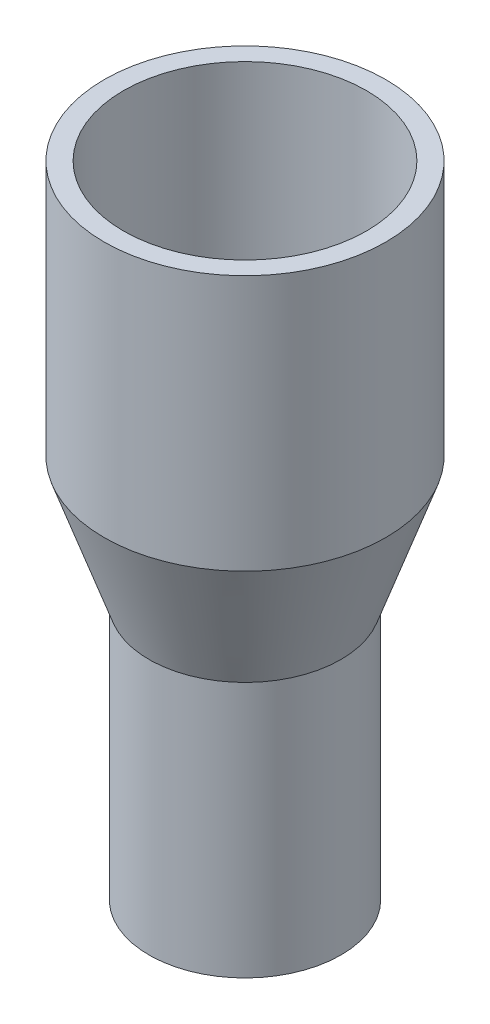
SolidWorks part; units mm, degrees
ref_plane "Front Plane" through (0, 0, 0) normal (0, 0, 1) x (1, 0, 0)
ref_plane "Top Plane" through (0, 0, 0) normal (0, 1, 0) x (1, 0, 0)
ref_plane "Right Plane" through (0, 0, 0) normal (1, 0, 0) x (0, 0, -1)
sketch "Sketch1" plane through (0, 0, 0) normal (0, 0, 1) x (1, 0, 0)
  line L0 (0, -25) -> (0, 25) construction
  line L1 (11, 25) -> (11, 5)
  line L2 (11, 5) -> (7.5, -5)
  line L3 (7.5, -5) -> (7.5, -25)
  line L4 (9.5, 25) -> (9.5, 5.2549)
  line L5 (9.5, 5.2549) -> (6, -4.7451)
  line L6 (6, -4.7451) -> (6, -25)
  line L7 (7.5, -5) -> (7.5, -60.9949) construction
  line L8 (6, -4.7451) -> (6, -60.9949) construction
  line L9 (7.5, -25) -> (6, -25)
  line L10 (9.5, 25) -> (11, 25)
  point P4 (0, 0)
  dimension "D2" = 11
  dimension "D3" = 50
  dimension "D4" = 15
  dimension "D5" = 20
  dimension "D6" = 20
  dimension "D1" = 1.5
revolve "Revolve1" add sketch "Sketch1" angle 360 about L0
